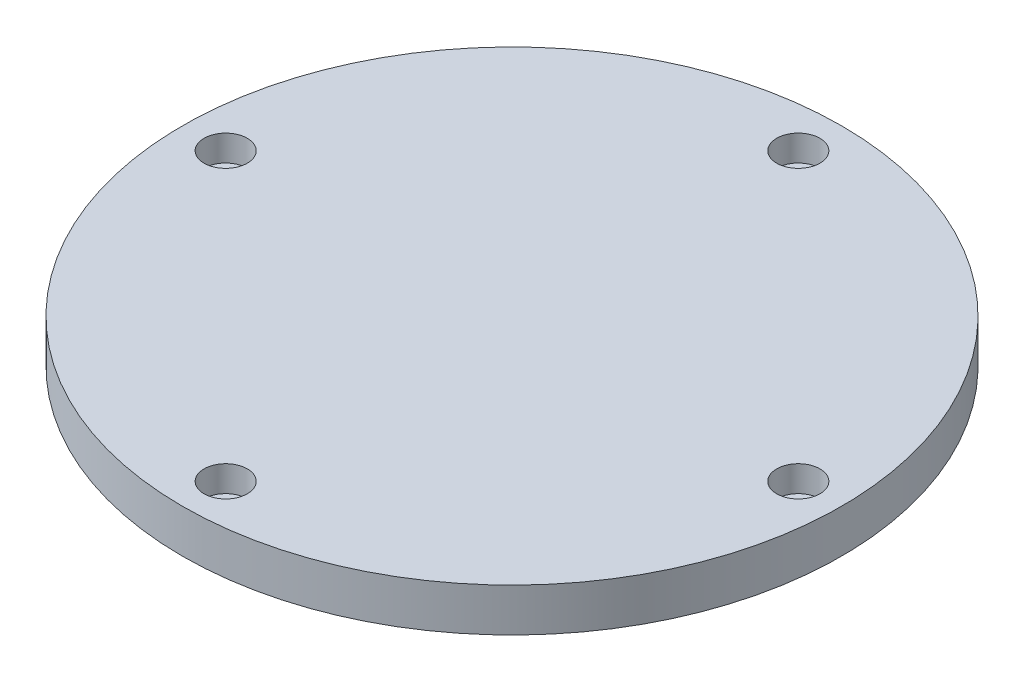
SolidWorks part; units mm, degrees
ref_plane "Front Plane" through (0, 0, 0) normal (0, 0, 1) x (1, 0, 0)
ref_plane "Top Plane" through (0, 0, 0) normal (0, 1, 0) x (1, 0, 0)
ref_plane "Right Plane" through (0, 0, 0) normal (1, 0, 0) x (0, 0, -1)
sketch "Sketch1" plane through (0, 0, 0) normal (0, 1, 0) x (1, 0, 0)
  circle A0 centre (0, 0) radius 38.1
  dimension "D1" = 76.2
extrude "Boss-Extrude1" add sketch "Sketch1" along normal blind 5
sketch "Sketch2" plane through (0, 5, 0) normal (0, 1, 0) x (1, 0, 0)
  line L0 (0, 0) -> (-38.1, 0) construction
  line L1 (38.1, 0) -> (0, 0) construction
  line L2 (0, 0) -> (0, 38.1) construction
  line L3 (0, 0) -> (0, -38.1) construction
  circle A0 centre (0, 0) radius 38.1 construction
  circle A1 centre (0, 0) radius 33.1 construction
  circle A2 centre (-33.1, 0) radius 2.5
  circle A3 centre (0, -33.1) radius 2.5
  circle A4 centre (33.1, 0) radius 2.5
  circle A5 centre (0, 33.1) radius 2.5
  dimension "D1" = 5
  dimension "D3" = 5
extrude "Cut-Extrude1" cut sketch "Sketch2" against normal blind 3
